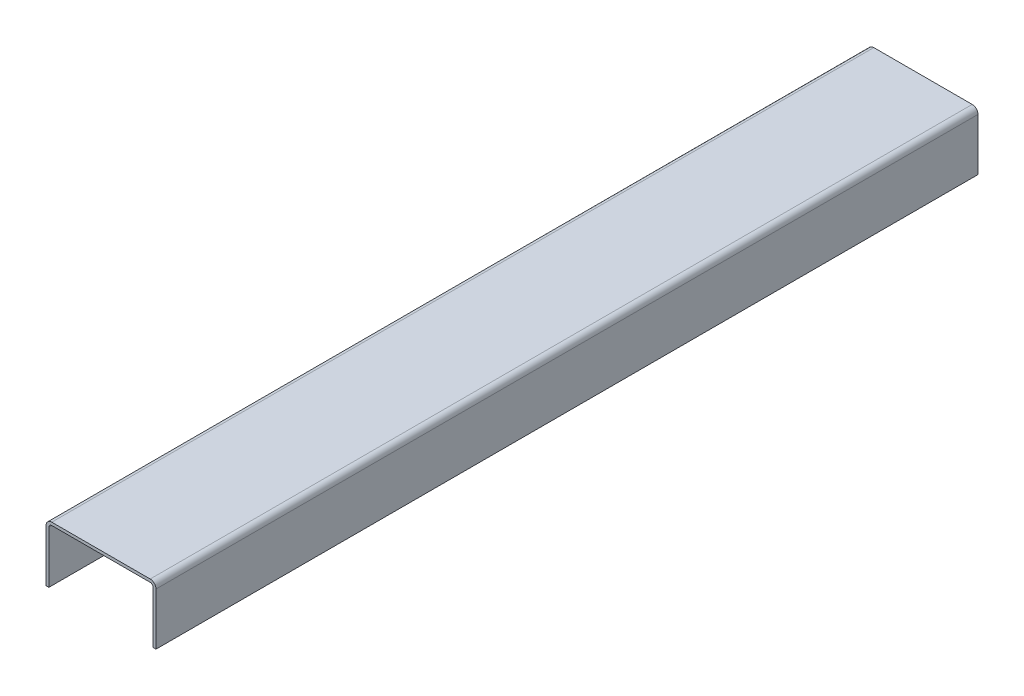
SolidWorks part; units mm, degrees
ref_plane "Front Plane" through (0, 0, 0) normal (0, 0, 1) x (1, 0, 0)
ref_plane "Top Plane" through (0, 0, 0) normal (0, 1, 0) x (1, 0, 0)
ref_plane "Right Plane" through (0, 0, 0) normal (1, 0, 0) x (0, 0, -1)
sketch "Sketch1" plane through (0, 0, 0) normal (0, 0, 1) x (1, 0, 0)
  line L0 (0, 0) -> (0, 18)
  line L1 (2, 20) -> (36, 20)
  line L2 (38, 18) -> (38, 0)
  line L3 (1, 0) -> (1, 18)
  line L4 (2, 19) -> (36, 19)
  line L5 (37, 18) -> (37, 0)
  line L6 (0, 0) -> (1, 0)
  line L7 (37, 0) -> (38, 0)
  arc A0 (0, 18) -> (2, 20) centre (2, 18) cw
  arc A1 (36, 20) -> (38, 18) centre (36, 18) cw
  arc A2 (1, 18) -> (2, 19) centre (2, 18) cw
  arc A3 (36, 19) -> (37, 18) centre (36, 18) cw
  point P8 (0, 20)
  point P11 (38, 20)
  dimension "D3" = 2
  dimension "D1" = 38
  dimension "D2" = 20
  dimension "D4" = 1
extrude "Boss-Extrude1" add sketch "Sketch1" along normal blind 284
